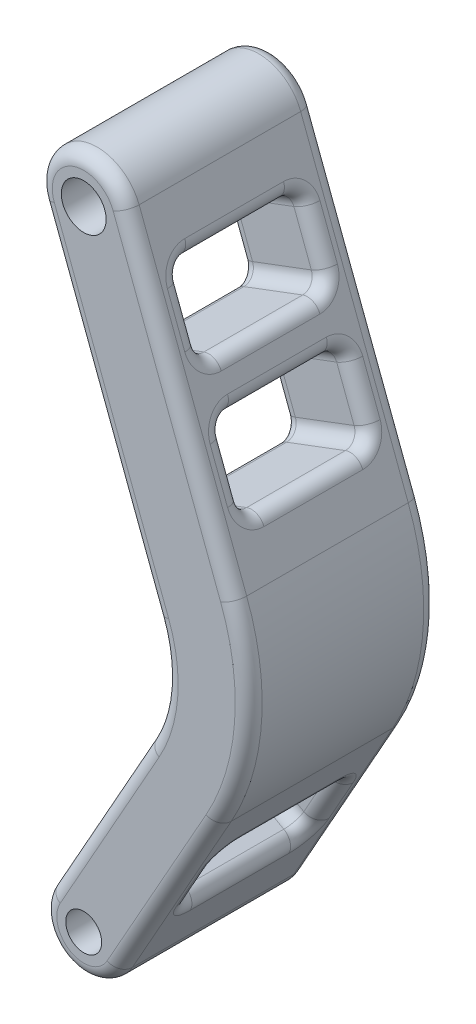
SolidWorks part; units mm, degrees
ref_plane "Front Plane" through (0, 0, 0) normal (0, 0, 1) x (1, 0, 0)
ref_plane "Top Plane" through (0, 0, 0) normal (0, 1, 0) x (1, 0, 0)
ref_plane "Right Plane" through (0, 0, 0) normal (1, 0, 0) x (0, 0, -1)
sketch "Sketch1" plane through (0, 0, 0) normal (0, 0, 1) x (1, 0, 0)
  line L0 (0, 0) -> (0, 140) construction
  line L1 (-7.8458, 4.4094) -> (14.2013, 43.6385)
  line L2 (16.1186, 68.9231) -> (-9.3567, 136.4712)
  line L3 (29.893, 34.8197) -> (7.8458, -4.4094)
  line L6 (33.3185, 79.9938) -> (9.3567, 143.5288)
  circle A0 centre (0, 0) radius 4
  arc A1 (-7.8458, 4.4094) -> (7.8458, -4.4094) centre (0, 0) ccw
  circle A2 centre (0, 140) radius 5
  arc A3 (9.3567, 143.5288) -> (-9.3567, 136.4712) centre (0, 140) ccw
  arc A4 (33.3185, 79.9938) -> (29.893, 34.8197) centre (-16.8323, 61.0797) cw
  arc A5 (14.2013, 43.6385) -> (16.1186, 68.9231) centre (-11.9514, 58.3366) ccw
  dimension "D1" = 8
  dimension "D2" = 18
  dimension "D3" = 140
  dimension "D4" = 10
  dimension "D6" = 130
  dimension "D5" = 20
  dimension "D7" = 30
  dimension "D8" = 45
  dimension "D9" = 45
extrude "Boss-Extrude1" add sketch "Sketch1" along normal blind 42
sketch "Sketch2" plane through (36.8684, 13.9047, 0) normal (-0.9357, -0.3529, 0) x (0, 0, 1)
  line L0 (42, 130.9936) -> (42, 58.8012) construction
  line L1 (7, 118.9936) -> (35, 118.9936)
  line L2 (7, 118.9936) -> (7, 101.9936)
  line L3 (7, 101.9936) -> (35, 101.9936)
  line L4 (35, 118.9936) -> (35, 101.9936)
  line L5 (7, 91.9936) -> (7, 74.9936)
  line L6 (35, 91.9936) -> (35, 74.9936)
  line L7 (7, 91.9936) -> (35, 91.9936)
  line L8 (7, 74.9936) -> (35, 74.9936)
  line L9 (0, 130.9936) -> (0, 58.8012) construction
  line L10 (42, 130.9936) -> (0, 130.9936) construction
  dimension "D1" = 7
  dimension "D2" = 7
  dimension "D3" = 12
  dimension "D4" = 17
  dimension "D5" = 17
  dimension "15" = 10
extrude "Cut-Extrude1" cut sketch "Sketch2" against normal blind 42
sketch "Sketch3" plane through (-7.8458, 4.4094, 0) normal (-0.8718, 0.4899, 0) x (0, 0, 1)
  line L0 (42, 45) -> (42, 0) construction
  line L1 (7, 32) -> (35, 32)
  line L2 (7, 32) -> (7, 15)
  line L3 (7, 15) -> (35, 15)
  line L4 (35, 32) -> (35, 15)
  line L5 (0, 45) -> (0, 0) construction
  line L6 (42, 0) -> (0, 0) construction
  dimension "D1" = 17
  dimension "D2" = 7
  dimension "D3" = 7
  dimension "D4" = 15
extrude "Cut-Extrude2" cut sketch "Sketch3" against normal blind 42
fillet "Fillet1" radius 3 52 edges at (36.6131, 57.027, 0) (18.8694, 15.2051, 0) (-4.4094, -7.8458, 0) (3.1777, 24.024, 0) (17.9627, 56.0683, 0) (3.381, 102.6971, 0) (-3.5288, 149.3567, 0) (18.8694, 15.2051, 42) (-4.4094, -7.8458, 42) (3.1777, 24.024, 42) (17.9627, 56.0683, 42) (21.3376, 111.7613, 0) (3.381, 102.6971, 42) (-3.5288, 149.3567, 42) (21.3376, 111.7613, 42) (36.6131, 57.027, 42) (23.5238, 23.4868, 21) (15.1949, 8.6669, 21) (-0.4968, 17.4858, 21) (7.8321, 32.3057, 21) (29.118, 91.1314, 21) (23.119, 107.0377, 21) (4.4057, 99.9801, 21) (10.4046, 84.0738, 21) (13.5913, 132.3008, 21) (19.5902, 116.3944, 21) (0.8769, 109.3368, 21) (-5.1221, 125.2432, 21) (19.3593, 16.0769, 35) (15.678, 27.8963, 35) (3.6677, 24.8957, 35) (7.349, 13.0764, 35) (19.3593, 16.0769, 7) (7.349, 13.0764, 7) (3.6677, 24.8957, 7) (15.678, 27.8963, 7) (26.1185, 99.0846, 7) (19.7613, 87.6026, 7) (7.4051, 92.0269, 7) (13.7623, 103.5089, 7) (26.1185, 99.0846, 35) (13.7623, 103.5089, 35) (7.4051, 92.0269, 35) (19.7613, 87.6026, 35) (16.5907, 124.3476, 35) (4.2346, 128.772, 35) (-2.1226, 117.29, 35) (10.2335, 112.8656, 35) (16.5907, 124.3476, 7) (10.2335, 112.8656, 7) (-2.1226, 117.29, 7) (4.2346, 128.772, 7)
